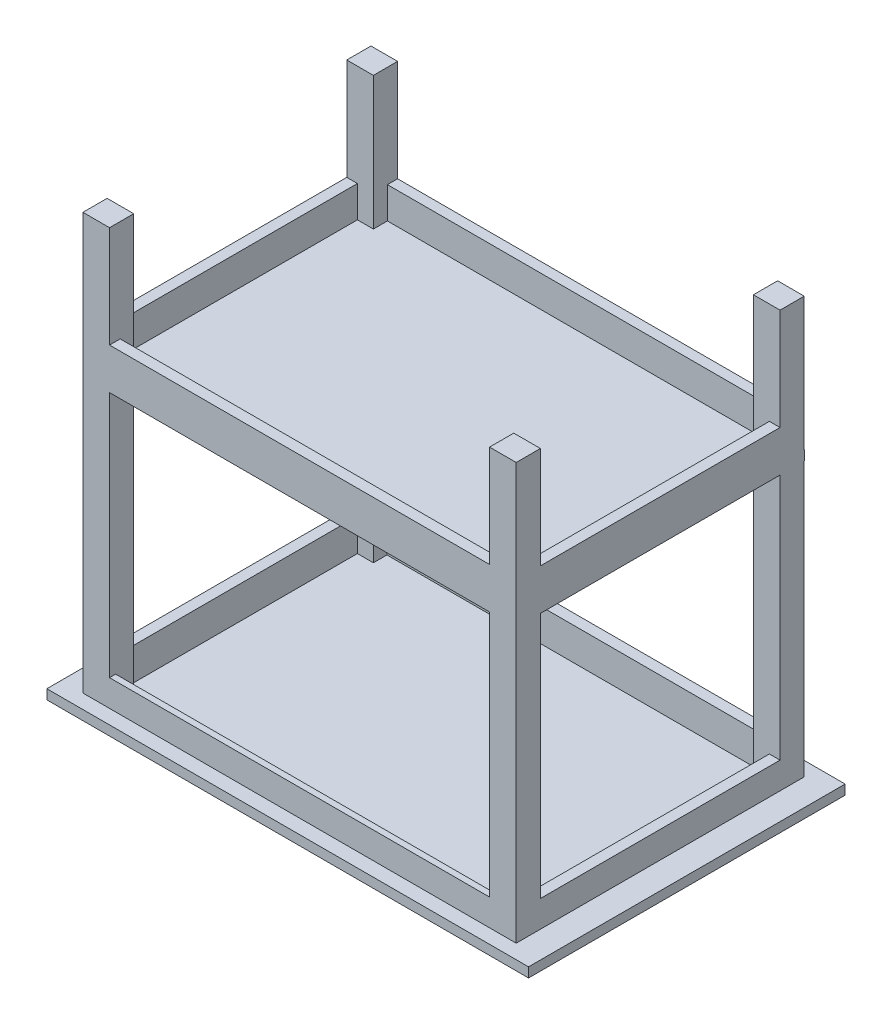
SolidWorks part; units mm, degrees
material "Haya"
ref_plane "Alzado" through (0, 0, 0) normal (0, 0, 1) x (1, 0, 0)
ref_plane "Planta" through (0, 0, 0) normal (0, 1, 0) x (1, 0, 0)
ref_plane "Vista lateral" through (0, 0, 0) normal (1, 0, 0) x (0, 0, -1)
sketch "Croquis2" plane through (0, 0, 0) normal (0, 1, 0) x (1, 0, 0)
  line L1 (-497.0522, 307.635) -> (497.9478, 307.635)
  line L2 (-497.0522, 307.635) -> (-497.0522, -346.365)
  line L3 (-497.0522, -346.365) -> (497.9478, -346.365)
  line L4 (497.9478, 307.635) -> (497.9478, -346.365)
  dimension "D1" = 995
  dimension "D2" = 654
extrude "Saliente-Extruir1" add sketch "Croquis2" along normal blind 20 contours L2 L1 L4 L3
sketch "Croquis4" plane through (0, 0, 0) normal (0, 1, 0) x (1, 0, 0)
  line L0 (497.9478, 307.635) -> (497.9478, -346.365) construction
  line L1 (-452.0522, 278.135) -> (442.9478, 278.135)
  line L2 (-452.0522, 278.135) -> (-452.0522, -316.865)
  line L3 (-452.0522, -316.865) -> (442.9478, -316.865)
  line L4 (442.9478, 278.135) -> (442.9478, -316.865)
  line L8 (-497.0522, 307.635) -> (-497.0522, -346.365) construction
  line L9 (-497.0522, -346.365) -> (497.9478, -346.365) construction
  line L10 (-497.0522, 307.635) -> (497.9478, 307.635) construction
  dimension "D1" = 895
  dimension "D2" = 595
  dimension "D3" = 55
  dimension "D4" = 45
  dimension "D5" = 29.5
  dimension "D6" = 29.5
extrude "Saliente-Extruir2" add sketch "Croquis4" along normal blind 75
sketch "Croquis6" plane through (0, 75, 0) normal (0, 1, 0) x (1, 0, 0)
  line L0 (442.9478, 278.135) -> (-452.0522, 278.135) construction
  line L1 (-430.0522, 256.135) -> (420.9478, 256.135)
  line L2 (-430.0522, 256.135) -> (-430.0522, -304.252)
  line L3 (-430.0522, -304.252) -> (420.9478, -304.252)
  line L4 (420.9478, 256.135) -> (420.9478, -304.252)
  line L5 (-452.0522, 278.135) -> (-452.0522, -316.865) construction
  line L6 (442.9478, -316.865) -> (442.9478, 278.135) construction
  dimension "D1" = 22
  dimension "D2" = 12.613
  dimension "D3" = 22
  dimension "D4" = 22
extrude "Cortar-Extruir1" cut sketch "Croquis6" against normal blind 67 contours L2 L1 L4 L3
sketch "Croquis7" plane through (0, 0, 0) normal (0, 1, 0) x (1, 0, 0)
  line L1 (-452.0522, -316.865) -> (-397.0522, -316.865)
  line L2 (-452.0522, -316.865) -> (-452.0522, -266.865)
  line L3 (-452.0522, -266.865) -> (-397.0522, -266.865)
  line L4 (-397.0522, -316.865) -> (-397.0522, -266.865)
  dimension "D1" = 55
  dimension "D2" = 50
extrude "Saliente-Extruir3" add sketch "Croquis7" along normal blind 880
sketch "Croquis9" plane through (0, 0, 0) normal (0, 1, 0) x (1, 0, 0)
  line L1 (-452.0522, 278.135) -> (-397.0522, 278.135)
  line L2 (-452.0522, 278.135) -> (-452.0522, 228.135)
  line L3 (-452.0522, 228.135) -> (-397.0522, 228.135)
  line L4 (-397.0522, 278.135) -> (-397.0522, 228.135)
  dimension "D1" = 55
  dimension "D2" = 50
extrude "Saliente-Extruir5" add sketch "Croquis9" along normal blind 880
sketch "Croquis10" plane through (0, 0, 0) normal (0, 1, 0) x (1, 0, 0)
  line L1 (442.9478, 278.135) -> (387.9478, 278.135)
  line L2 (442.9478, 278.135) -> (442.9478, 228.135)
  line L3 (442.9478, 228.135) -> (387.9478, 228.135)
  line L4 (387.9478, 278.135) -> (387.9478, 228.135)
  dimension "D1" = 50
  dimension "D2" = 55
extrude "Saliente-Extruir6" add sketch "Croquis10" along normal blind 880
sketch "Croquis11" plane through (0, 0, 0) normal (0, 1, 0) x (1, 0, 0)
  line L1 (442.9478, -316.865) -> (387.9478, -316.865)
  line L2 (442.9478, -316.865) -> (442.9478, -266.865)
  line L3 (442.9478, -266.865) -> (387.9478, -266.865)
  line L4 (387.9478, -316.865) -> (387.9478, -266.865)
  dimension "D1" = 55
  dimension "D2" = 50
extrude "Saliente-Extruir7" add sketch "Croquis11" along normal blind 880
sketch "Croquis14" plane through (0, 0, 316.865) normal (0, 0, 1) x (1, 0, 0)
  line L0 (-452.0522, 605) -> (442.9478, 605)
  line L1 (-452.0522, 880) -> (-452.0522, 20) construction
  line L2 (442.9478, 880) -> (442.9478, 20) construction
  line L3 (-452.0522, 20) -> (442.9478, 20) construction
  dimension "D1" = 585
sketch "Croquis17" plane through (-452.0522, 0, 0) normal (-1, 0, 0) x (0, 0, 1)
extrude "Extruir-Lámina4" add sketch "Croquis14" against normal blind 596 thin
sketch "Croquis22" plane through (0, 605, 0) normal (0, 1, 0) x (1, 0, 0)
  line L1 (-452.0522, 278.135) -> (442.9478, 278.135)
  line L2 (-452.0522, 278.135) -> (-452.0522, -316.865)
  line L3 (-452.0522, -316.865) -> (442.9478, -316.865)
  line L4 (442.9478, 278.135) -> (442.9478, -316.865)
extrude "Saliente-Extruir8" add sketch "Croquis22" along normal blind 65
sketch "Croquis25" plane through (0, 670, 0) normal (0, 1, 0) x (1, 0, 0)
  line L0 (442.9478, -266.865) -> (442.9478, 228.135) construction
  line L1 (-430.0522, 228.135) -> (420.9478, 228.135)
  line L2 (-430.0522, 228.135) -> (-430.0522, -266.865)
  line L3 (-430.0522, -266.865) -> (420.9478, -266.865)
  line L4 (420.9478, 228.135) -> (420.9478, -266.865)
  line L5 (-452.0522, 278.135) -> (-452.0522, -316.865) construction
  dimension "D1" = 22
  dimension "D2" = 22
extrude "Cortar-Extruir2" cut sketch "Croquis25" against normal blind 65
sketch "Croquis26" plane through (0, 670, 0) normal (0, 1, 0) x (1, 0, 0)
  line L0 (-452.0522, 279.135) -> (442.9478, 279.135) construction
  line L1 (-397.0522, -294.865) -> (387.9478, -294.865)
  line L2 (-397.0522, -294.865) -> (-397.0522, 257.135)
  line L3 (-397.0522, 257.135) -> (387.9478, 257.135)
  line L4 (387.9478, -294.865) -> (387.9478, 257.135)
  line L5 (-397.0522, -316.865) -> (387.9478, -316.865) construction
  dimension "D1" = 22
  dimension "D2" = 22
extrude "Cortar-Extruir3" cut sketch "Croquis26" against normal blind 65
